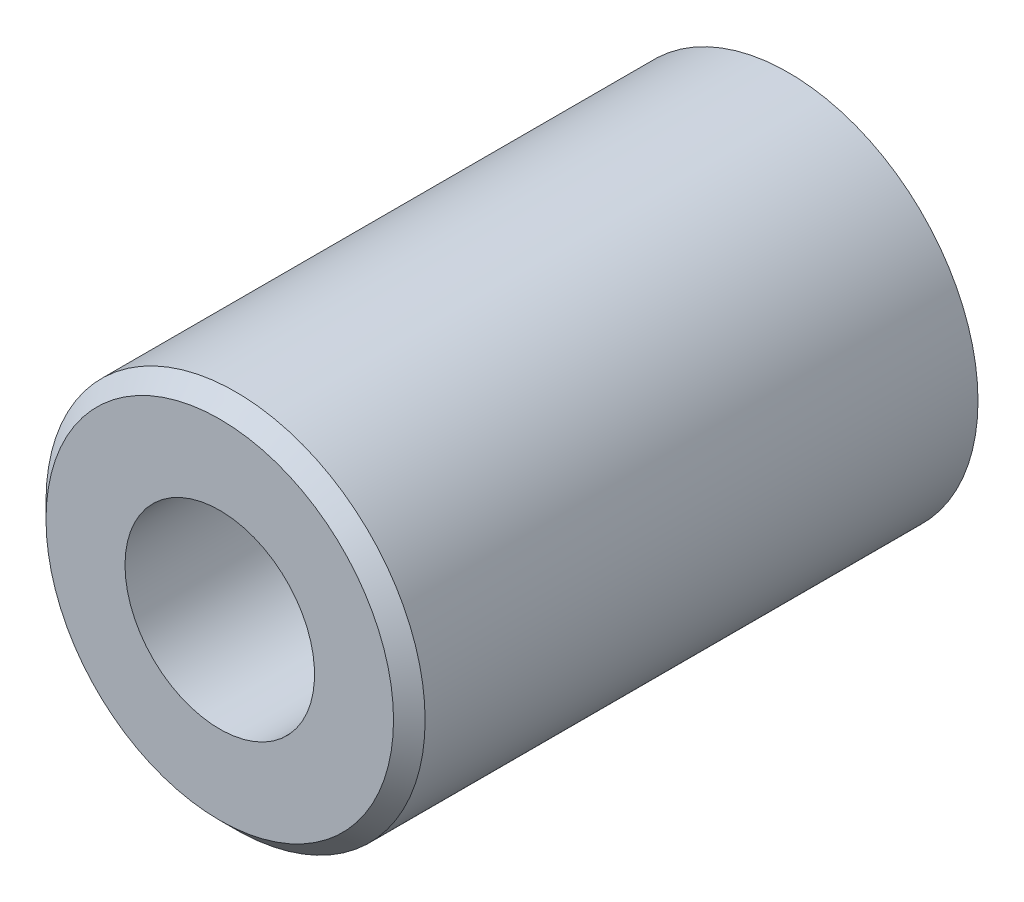
SolidWorks part; units mm, degrees
ref_plane "Front Plane" through (0, 0, 0) normal (0, 0, 1) x (1, 0, 0)
ref_plane "Top Plane" through (0, 0, 0) normal (0, 1, 0) x (1, 0, 0)
ref_plane "Right Plane" through (0, 0, 0) normal (1, 0, 0) x (0, 0, -1)
sketch "Sketch1" plane through (0, 0, 0) normal (0, 0, 1) x (1, 0, 0)
  line L0 (0, 1.5875) -> (0, 3.175) construction
  circle A0 centre (0, 0) radius 3.175
  circle A1 centre (0, 0) radius 1.5875
  dimension "OD" = 6.35
  dimension "ID" = 3.175
  dimension "D1" = 1.5875
extrude "Extrude1" add sketch "Sketch1" along normal mid plane 9.525
chamfer "Chamfer1" distance 0.2646 angle 45 1 edges at (3.175, 0, 4.7625)
sketch "Sketch6" plane through (0, 0, 4.7625) normal (0, 0, -1) x (-1, 0, 0)
  line L0 (0, 0) -> (-1.5875, 0) construction
  line L1 (0, 0) -> (1.1225, 1.1225) construction
  circle A0 centre (0, 0) radius 1.5875 construction
  circle A3 centre (0, 0) radius 1.5875
  dimension "D1" = 135
equation "\"D1@Chamfer1\" = \"D1@Sketch1\"/6"
